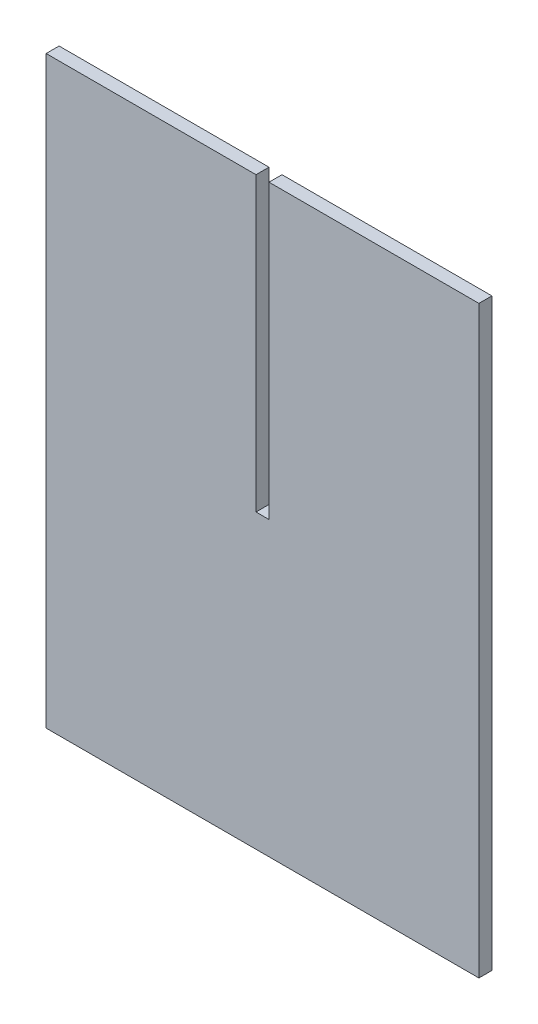
SolidWorks part; units mm, degrees
ref_plane "Front Plane" through (0, 0, 0) normal (0, 0, 1) x (1, 0, 0)
ref_plane "Top Plane" through (0, 0, 0) normal (0, 1, 0) x (1, 0, 0)
ref_plane "Right Plane" through (0, 0, 0) normal (1, 0, 0) x (0, 0, -1)
sketch "Sketch1" plane through (0, 0, 0) normal (0, 0, 1) x (1, 0, 0)
  line L1 (-50, -67.5) -> (50, -67.5)
  line L2 (-50, -67.5) -> (-50, 67.5)
  line L3 (-50, 67.5) -> (50, 67.5)
  line L4 (50, -67.5) -> (50, 67.5)
  line L5 (-50, -67.5) -> (50, 67.5) construction
  line L6 (-50, 67.5) -> (50, -67.5) construction
  point P0 (0, 0)
  dimension "D1" = 100
  dimension "D2" = 135
extrude "Boss-Extrude1" add sketch "Sketch1" along normal blind 3 contours L2 L3 L4 L1
sketch "Sketch2" plane through (0, 0, 3) normal (0, 0, 1) x (1, 0, 0)
  line L2 (1.5, 0) -> (1.5, 67.5)
  line L3 (-1.5, 0) -> (-1.5, 67.5)
  line L4 (-1.5, 67.5) -> (1.5, 67.5)
  line L5 (-1.5, 0) -> (1.5, 0)
extrude "Cut-Extrude1" cut sketch "Sketch2" against normal blind 3
